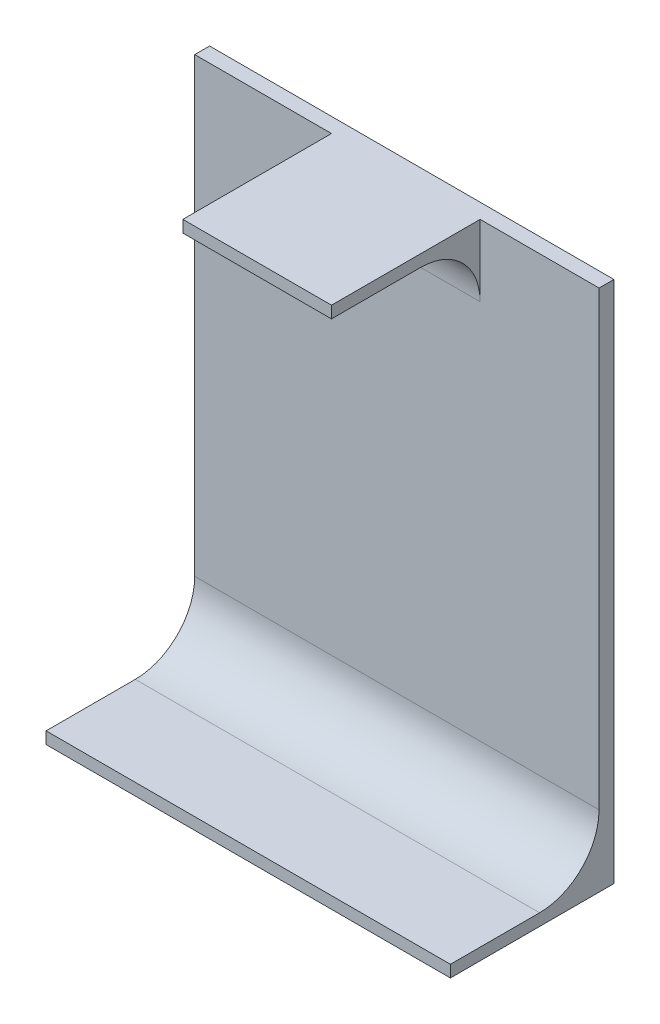
SolidWorks part; units mm, degrees
ref_plane "Front Plane" through (0, 0, 0) normal (0, 0, 1) x (1, 0, 0)
ref_plane "Top Plane" through (0, 0, 0) normal (0, 1, 0) x (1, 0, 0)
ref_plane "Right Plane" through (0, 0, 0) normal (1, 0, 0) x (0, 0, -1)
sketch "Sketch1" plane through (0, 0, 0) normal (0, 0, 1) x (1, 0, 0)
  line L1 (0, 0) -> (-68, 0)
  line L2 (0, 0) -> (0, -88)
  line L3 (0, -88) -> (-68, -88)
  line L4 (-68, 0) -> (-68, -88)
  dimension "D1" = 88
  dimension "D2" = 68
extrude "Boss-Extrude1" add sketch "Sketch1" along normal blind 25 and the other way blind 2.5
sketch "Sketch2" plane through (0, 0, 25) normal (0, 0, 1) x (1, 0, 0)
  line L0 (0, 0) -> (-68, 0) construction
  line L1 (-75.1787, -2) -> (7.3317, -2)
  line L2 (-75.1787, -2) -> (-75.1787, -86)
  line L3 (-75.1787, -86) -> (7.3317, -86)
  line L4 (7.3317, -2) -> (7.3317, -86)
  line L6 (-68, -88) -> (0, -88) construction
  dimension "D1" = 2
  dimension "D3" = 2
extrude "Cut-Extrude1" cut sketch "Sketch2" against normal blind 25
sketch "Sketch3" plane through (0, 0, 0) normal (0, 1, 0) x (1, 0, 0)
  line L0 (-68, 2.5) -> (-68, -25) construction
  line L1 (-68, -25) -> (-45, -25)
  line L2 (-68, -25) -> (-68, 0)
  line L3 (-68, 0) -> (-45, 0)
  line L4 (-45, -25) -> (-45, 0)
  line L5 (0, 2.5) -> (-68, 2.5) construction
  line L6 (0, 2.5) -> (0, -25) construction
  point P8 (0, 0)
  dimension "D1" = 2.5
  dimension "D2" = 45
extrude "Cut-Extrude2" cut sketch "Sketch3" against normal blind 25 contours L2 L1 L4 L3
sketch "Sketch4" plane through (0, 0, 0) normal (0, 1, 0) x (1, 0, 0)
  line L1 (0, -25) -> (-20, -25)
  line L2 (0, -25) -> (0, 0)
  line L3 (0, 0) -> (-20, 0)
  line L4 (-20, -25) -> (-20, 0)
  dimension "D1" = 25
  dimension "D2" = 20
extrude "Cut-Extrude3" cut sketch "Sketch4" against normal blind 25
fillet "Fillet2" radius 10 2 edges at (-34, -86, 0) (-32.5, -2, 0)
